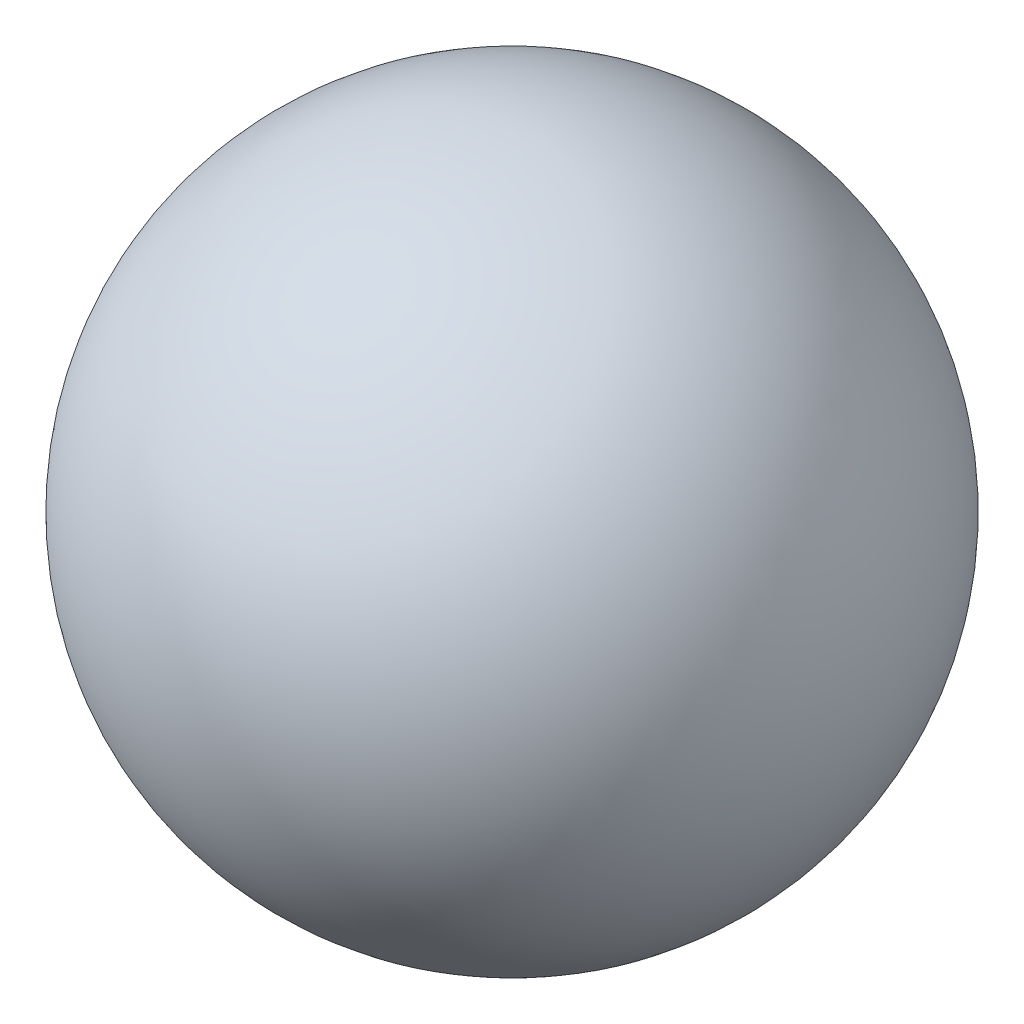
SolidWorks part; units mm, degrees
ref_plane "Front Plane" through (0, 0, 0) normal (0, 0, 1) x (1, 0, 0)
ref_plane "Top Plane" through (0, 0, 0) normal (0, 1, 0) x (1, 0, 0)
ref_plane "Right Plane" through (0, 0, 0) normal (1, 0, 0) x (0, 0, -1)
sketch "Sketch2" plane through (0, 0, 0) normal (0, 0, 1) x (1, 0, 0)
  line L0 (0, 101.6) -> (0, -101.6) construction
  line L1 (0, 101.6) -> (0, -101.6)
  arc A0 (0, 101.6) -> (0, -101.6) centre (0, 0) cw
  dimension "D1" = 101.6
revolve "Revolve1" add sketch "Sketch2" angle 360 about L0
